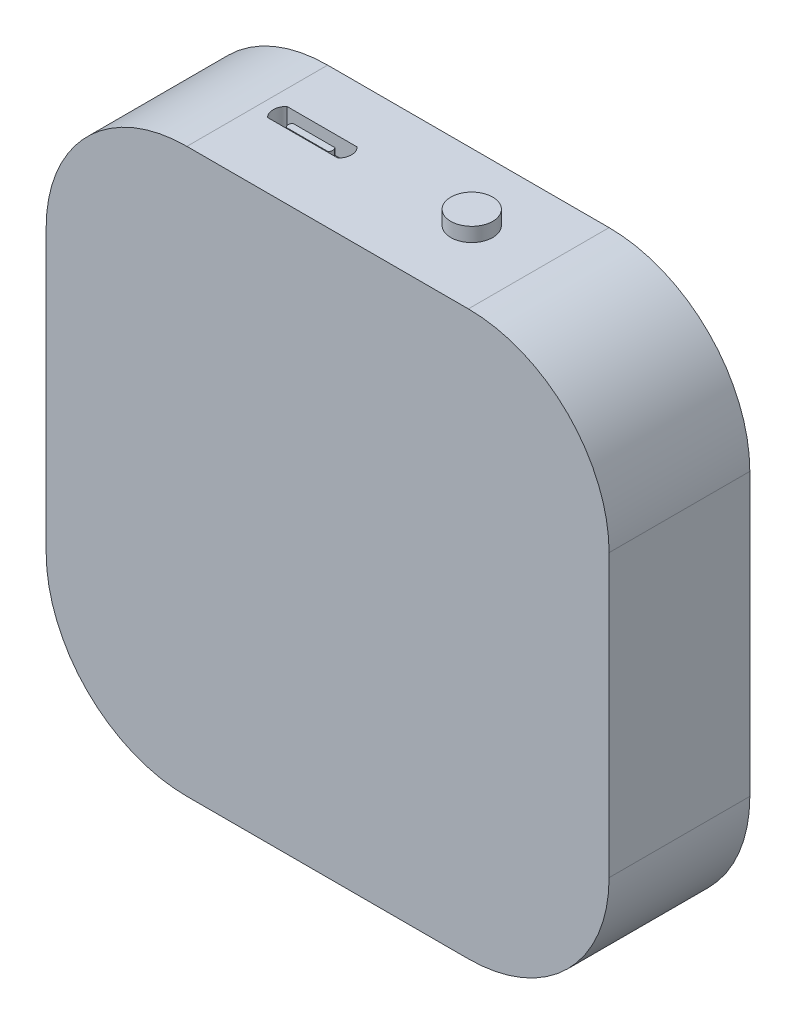
SolidWorks part; units mm, degrees
ref_plane "Front Plane" through (0, 0, 0) normal (0, 0, 1) x (1, 0, 0)
ref_plane "Top Plane" through (0, 0, 0) normal (0, 1, 0) x (1, 0, 0)
ref_plane "Right Plane" through (0, 0, 0) normal (1, 0, 0) x (0, 0, -1)
sketch "Sketch1" plane through (0, 0, 0) normal (0, 0, 1) x (1, 0, 0)
  line L1 (-7.7885, 11.6346) -> (32.2115, 11.6346)
  line L2 (-7.7885, 11.6346) -> (-7.7885, -28.3654)
  line L3 (-7.7885, -28.3654) -> (32.2115, -28.3654)
  line L4 (32.2115, 11.6346) -> (32.2115, -28.3654)
  dimension "D1" = 40
  dimension "D2" = 40
extrude "Boss-Extrude2" add sketch "Sketch1" against normal blind 10
sketch "Sketch7" plane through (0, 0, -10) normal (0, 0, -1) x (-1, 0, 0)
  line L0 (-32.2115, 11.6346) -> (7.7885, 11.6346) construction
  line L1 (7.7885, 11.6346) -> (7.7885, -28.3654) construction
  line L2 (7.7885, -28.3654) -> (-32.2115, -28.3654) construction
  line L3 (-32.2115, -28.3654) -> (-32.2115, 11.6346) construction
  circle A0 centre (-12.2115, -8.3654) radius 12.5
  point P8 (-12.2115, -28.3654)
  point P11 (-32.2115, -8.3654)
  dimension "D1" = 25
  dimension "D2" = 20
  dimension "D3" = 20
  dimension "D4" = 20
  dimension "D5" = 20
extrude "Boss-Extrude3" add sketch "Sketch7" along normal blind 11
chamfer "Chamfer4" distance 4 angle 45 1 edges at (-0.2885, -8.3654, -21)
sketch "Sketch10" plane through (0, 0, -21) normal (0, 0, -1) x (-1, 0, 0)
  circle A0 centre (-12.1268, -8.5632) radius 4
  dimension "D1" = 8
extrude "Cut-Extrude2" cut sketch "Sketch10" against normal blind 1
sketch "Sketch11" plane through (0, 0, 0) normal (0, 0, 1) x (1, 0, 0)
  circle A0 centre (-3.8093, 7.5424) radius 2.5
  dimension "D1" = 5
extrude "Cut-Extrude3" cut sketch "Sketch11" against normal blind 2
fillet "Fillet2" radius 10 1 edges at (32.2115, 11.6346, -5)
fillet "Fillet3" radius 10 3 edges at (-1.3093, 7.5424, -2) (-1.3093, 7.5424, 0) (-7.7885, 11.6346, -5)
fillet "Fillet4" radius 10 1 edges at (-7.7885, -28.3654, -5)
fillet "Fillet5" radius 10 1 edges at (32.2115, -28.3654, -5)
sketch "Sketch13" plane through (0, 11.6346, 0) normal (0, 1, 0) x (1, 0, 0)
  line L0 (3.3031, 4.6421) -> (8.2989, 4.6421)
  line L1 (3.3031, 6.0126) -> (8.2989, 6.0126)
  arc A0 (8.2989, 6.0126) -> (8.2989, 4.6421) centre (7.6136, 5.3274) cw
  arc A1 (3.3031, 6.0126) -> (3.3031, 4.6421) centre (3.9884, 5.3274) ccw
extrude "Cut-Extrude4" cut sketch "Sketch13" against normal blind 1.3
sketch "Sketch14" plane through (0, 10.3346, 0) normal (0, 1, 0) x (1, 0, 0)
  line L0 (4.2757, 5.4821) -> (7.2378, 5.4821)
  line L1 (4.2757, 4.9958) -> (7.2378, 4.9958)
  arc A0 (7.2378, 5.4821) -> (7.2378, 4.9958) centre (6.9947, 5.2389) cw
  arc A1 (4.2757, 4.9958) -> (4.2757, 5.4821) centre (4.5189, 5.2389) cw
extrude "Boss-Extrude5" add sketch "Sketch14" along normal blind 1
sketch "Sketch16" plane through (0, 11.6346, 0) normal (0, 1, 0) x (1, 0, 0)
  circle A0 centre (17.1987, 5.2538) radius 1.4908
extrude "Boss-Extrude6" add sketch "Sketch16" along normal blind 1
sketch "Sketch17" plane through (0, 0, -20) normal (0, 0, -1) x (-1, 0, 0)
  circle A0 centre (-12.1268, -8.5632) radius 1.3185
extrude "Cut-Extrude5" cut sketch "Sketch17" against normal blind 1
